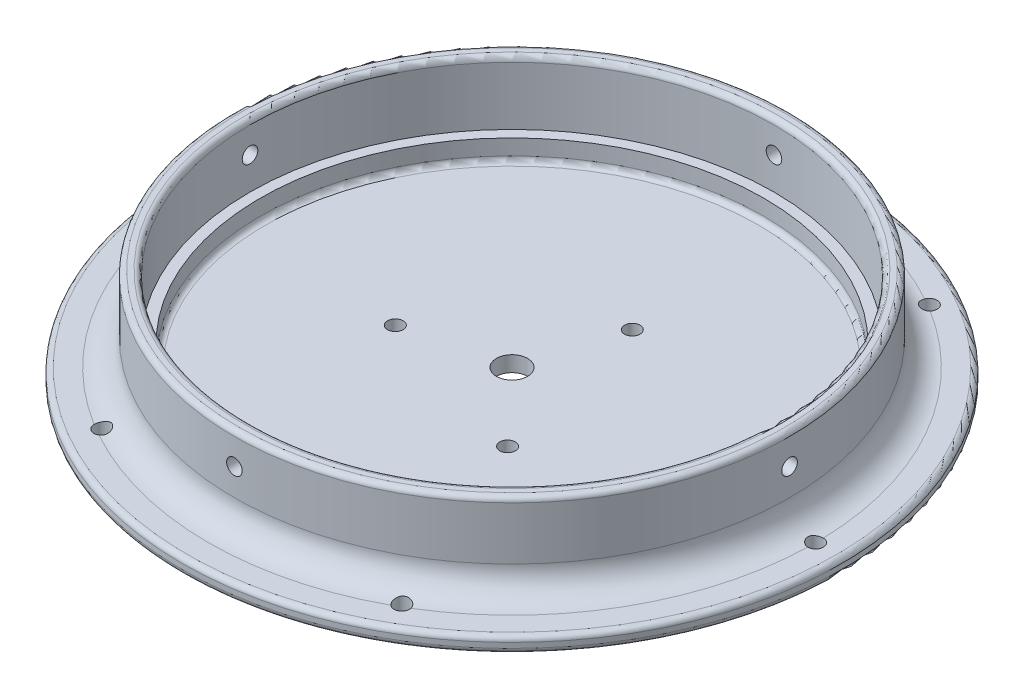
SolidWorks part; units mm, degrees
material "ABS PC"
ref_plane "Front Plane" through (0, 0, 0) normal (0, 0, 1) x (1, 0, 0)
ref_plane "Top Plane" through (0, 0, 0) normal (0, 1, 0) x (1, 0, 0)
ref_plane "Right Plane" through (0, 0, 0) normal (1, 0, 0) x (0, 0, -1)
sketch "Sketch1" plane through (0, 0, 0) normal (0, 0, 1) x (1, 0, 0)
  line L0 (0, 0) -> (0, 54.9) construction
  line L1 (0, 0) -> (0, 3)
  line L2 (0, 3) -> (47.5, 3)
  line L3 (48.5, 4) -> (48.5, 7)
  line L4 (48.5, 7) -> (50.5, 7)
  line L5 (50.5, 7) -> (50.5, 17)
  line L7 (50.5, 17) -> (50.5, 18.2075)
  line L8 (51.5, 19.2075) -> (52.5, 19.2075)
  line L9 (53.5, 18.2075) -> (53.5, 8)
  line L10 (38, 0) -> (0, 0)
  line L11 (38, 0) -> (62.5, 0)
  line L12 (63.5, 1) -> (63.5, 2)
  line L13 (62.5, 3) -> (58.5, 3)
  arc A0 (63.5, 2) -> (62.5, 3) centre (62.5, 2) ccw
  arc A1 (47.5, 3) -> (48.5, 4) centre (47.5, 4) ccw
  arc A2 (50.5, 18.2075) -> (51.5, 19.2075) centre (51.5, 18.2075) cw
  arc A3 (52.5, 19.2075) -> (53.5, 18.2075) centre (52.5, 18.2075) cw
  arc A4 (62.5, 0) -> (63.5, 1) centre (62.5, 1) ccw
  arc A5 (53.5, 8) -> (58.5, 3) centre (58.5, 8) ccw
  point P23 (63.5, 3)
  point P26 (63.5, 0)
  point P29 (53.5, 3)
  dimension "D9" = 3
  dimension "D11" = 1
  dimension "D12" = 5
  dimension "D1" = 10
  dimension "D2" = 50.5
  dimension "D3" = 3
  dimension "D5" = 2
  dimension "D6" = 3
  dimension "D7" = 7
  dimension "D10" = 10
revolve "Revolve1" add sketch "Sketch1" angle 360 about L0
sketch "Sketch3" plane through (0, 3, 0) normal (0, 1, 0) x (1, 0, 0)
  circle A0 centre (58.5, 0) radius 1.5
  circle A1 centre (0, 0) radius 63.5 construction
  circle A2 centre (29, -50.2295) radius 1.5
  circle A3 centre (-29.25, -49.7965) radius 1.5
  circle A4 centre (-58, 0.866) radius 1.5
  circle A5 centre (-28.5, 51.0955) radius 1.5
  circle A6 centre (29.75, 50.6625) radius 1.5
  point P4 (63.5, 0)
  point P17 (0.25, 0.433)
  dimension "D1" = 3
  dimension "D2" = 5
  dimension "D3" = 6
extrude "Cut-Extrude3" cut sketch "Sketch3" against normal through all both and the other way through all
sketch "Sketch4" plane through (0, 3, 0) normal (0, 1, 0) x (1, 0, 0)
  line L0 (0, 0) -> (26.6073, 0) construction
  line L1 (0, 0) -> (-13.3036, -23.0426) construction
  line L2 (0, 0) -> (-13.3036, 23.0426) construction
  circle A0 centre (0, 0) radius 13.65 construction
  circle A1 centre (5.289, 17.8843) radius 1.5
  circle A2 centre (12.7554, -13.606) radius 1.5
  circle A3 centre (-18.2751, -4.2033) radius 1.5
  circle A4 centre (0, 0) radius 3
  point P7 (0, 0)
  dimension "D2" = 27.3
  dimension "D3" = 3
  dimension "D4" = 3
  dimension "D5" = 3
  dimension "D6" = 6
  dimension "D1" = 3
extrude "Cut-Extrude4" cut sketch "Sketch4" against normal through all both and the other way through all
sketch "Sketch5" plane through (0, 0, 0) normal (0, 0, 1) x (1, 0, 0)
  line L0 (51.5, 19.2075) -> (-51.5, 19.2075) construction
  circle A0 centre (0, 13.2075) radius 1.5
  dimension "D1" = 3
  dimension "D2" = 6
extrude "Cut-Extrude5" cut sketch "Sketch5" against normal blind 80
pattern_circular "CirPattern1" count 4 over 360 of "Cut-Extrude5"
